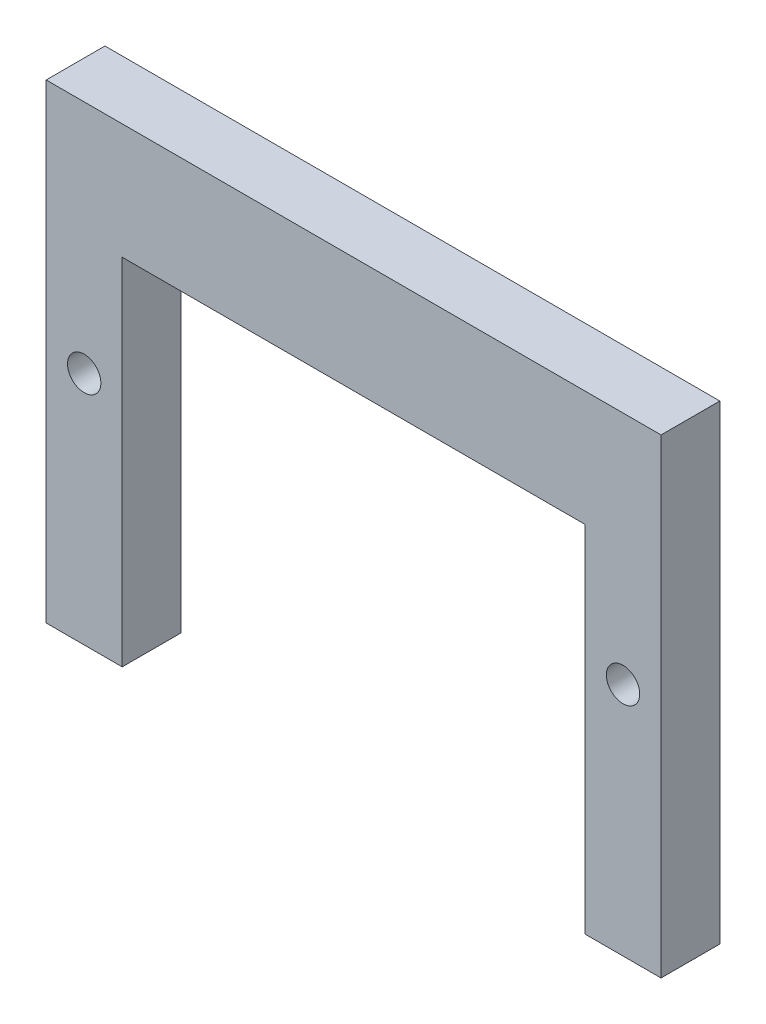
SolidWorks part; units mm, degrees
ref_plane "Front Plane" through (0, 0, 0) normal (0, 0, 1) x (1, 0, 0)
ref_plane "Top Plane" through (0, 0, 0) normal (0, 1, 0) x (1, 0, 0)
ref_plane "Right Plane" through (0, 0, 0) normal (1, 0, 0) x (0, 0, -1)
sketch "Sketch1" plane through (0, 0, 0) normal (0, 0, 1) x (1, 0, 0)
  line L0 (15.691, 24.0041) -> (-15.691, 24.0041)
  line L1 (-15.691, 24.0041) -> (-15.691, 0)
  line L2 (-15.691, 0) -> (-11.811, 0)
  line L3 (-11.811, 0) -> (-11.811, 18.1091)
  line L4 (-11.811, 18.1091) -> (11.811, 18.1091)
  line L5 (0, 81.0888) -> (0, 0) construction
  line L6 (11.811, 0) -> (11.811, 18.1091)
  line L7 (15.691, 0) -> (11.811, 0)
  line L8 (15.691, 24.0041) -> (15.691, 0)
  circle A0 centre (-13.751, 12.0021) radius 0.8509
  circle A1 centre (13.751, 12.0021) radius 0.8509
  point P14 (0, 18.1091)
  point P17 (0, 24.0041)
  dimension "D7" = 1.7018
  dimension "D1" = 3.88
  dimension "D2" = 24.0041
  dimension "D3" = 18.1091
  dimension "D4" = 11.811
  dimension "D5" = 12.0021
  dimension "D6" = 1.94
extrude "Boss-Extrude1" add sketch "Sketch1" along normal blind 3
